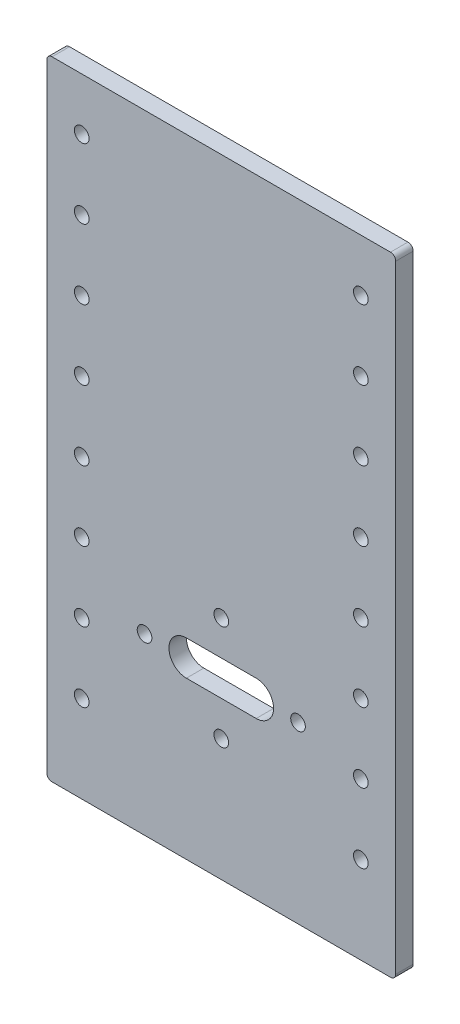
SolidWorks part; units mm, degrees
material "Thornel Mat VMA"
ref_plane "Front Plane" through (0, 0, 0) normal (0, 0, 1) x (1, 0, 0)
ref_plane "Top Plane" through (0, 0, 0) normal (0, 1, 0) x (1, 0, 0)
ref_plane "Right Plane" through (0, 0, 0) normal (1, 0, 0) x (0, 0, -1)
sketch "Sketch1" plane through (0, 0, 0) normal (0, 0, 1) x (1, 0, 0)
  line L1 (-50, -90) -> (50, -90)
  line L2 (-50, -90) -> (-50, 90)
  line L3 (-50, 90) -> (50, 90)
  line L4 (50, -90) -> (50, 90)
  line L5 (-50, -90) -> (50, 90) construction
  line L6 (-50, 90) -> (50, -90) construction
  point P0 (0, 0)
  dimension "D1" = 180
  dimension "D2" = 100
extrude "Boss-Extrude1" add sketch "Sketch1" along normal blind 5
sketch "Sketch2" plane through (0, 0, 0) normal (0, 0, -1) x (-1, 0, 0)
  line L0 (0, -90) -> (0, -40) construction
  line L1 (50, -90) -> (-50, -90) construction
  line L2 (-10, -40) -> (10, -40) construction
  line L3 (-10, -40) -> (10, -40) construction
  line L4 (-10, -35) -> (10, -35)
  line L5 (-10, -45) -> (10, -45)
  arc A0 (-10, -35) -> (-10, -45) centre (-10, -40) ccw
  arc A1 (10, -45) -> (10, -35) centre (10, -40) ccw
  circle A2 centre (-22, -40) radius 2.1
  circle A3 centre (0, -25) radius 2.1
  circle A4 centre (22, -40) radius 2.1
  circle A5 centre (0, -55) radius 2.1
  point P5 (0, -40)
  point P8 (0, -40)
  point P15 (5.2101, -50)
  dimension "D3" = 5
  dimension "D4" = 4.2
  dimension "D5" = 12
  dimension "D6" = 10
  dimension "D1" = 50
  dimension "D2" = 20
extrude "Cut-Extrude1" cut sketch "Sketch2" against normal through all
fillet "Fillet1" radius 1.5 4 edges at (50, -90, 2.5) (-50, -90, 2.5) (-50, 90, 2.5) (50, 90, 2.5)
sketch "Sketch3" plane through (0, 0, 0) normal (0, 0, -1) x (-1, 0, 0)
  line L0 (0, -22.9) -> (0, 90) construction
  line L1 (-48.5, 90) -> (48.5, 90) construction
  line L2 (-40, 90) -> (-40, -90) construction
  line L3 (48.5, -90) -> (-48.5, -90) construction
  line L4 (-50, -88.5) -> (-50, 88.5) construction
  circle A0 centre (0, -25) radius 2.1 construction
  circle A1 centre (-40, 75) radius 2.1
  circle A2 centre (-40, 55) radius 2.1
  circle A3 centre (-40, 35) radius 2.1
  circle A4 centre (-40, 15) radius 2.1
  circle A5 centre (-40, -5) radius 2.1
  circle A6 centre (40, -5) radius 2.1
  circle A7 centre (40, 15) radius 2.1
  circle A8 centre (40, 35) radius 2.1
  circle A9 centre (40, 75) radius 2.1
  circle A10 centre (40, 55) radius 2.1
  circle A11 centre (-40, -25) radius 2.1
  circle A12 centre (-40, -45) radius 2.1
  circle A13 centre (-40, -65) radius 2.1
  circle A14 centre (40, -65) radius 2.1
  circle A15 centre (40, -45) radius 2.1
  circle A16 centre (40, -25) radius 2.1
  dimension "D1" = 4.2
  dimension "D3" = 15
  dimension "D5" = 20
  dimension "D2" = 10
  dimension "D4" = 8
extrude "Cut-Extrude2" cut sketch "Sketch3" against normal through all
